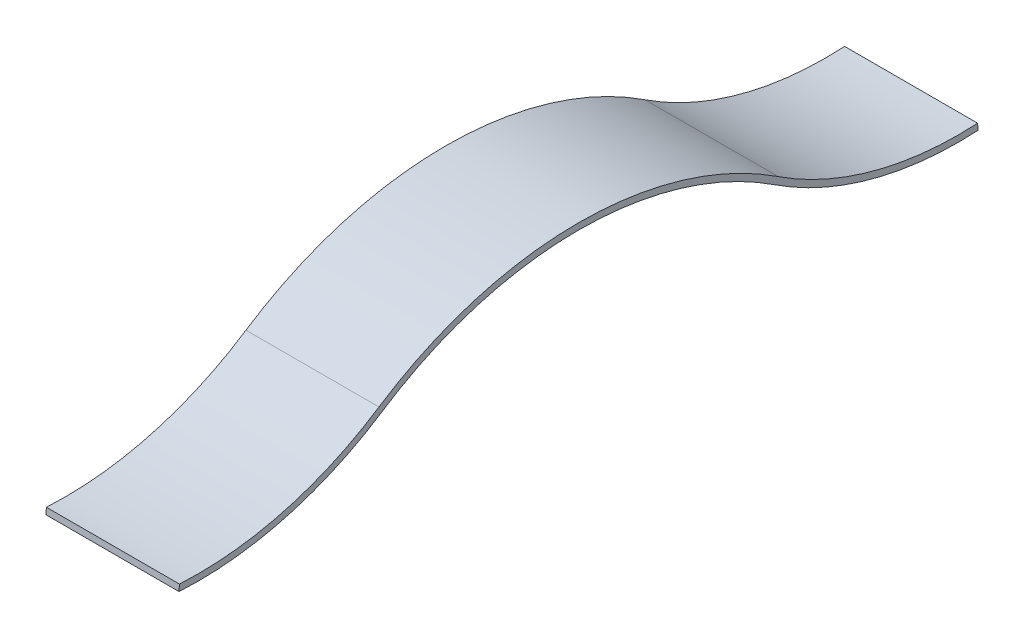
SolidWorks part; units mm, degrees
ref_plane "Front Plane" through (0, 0, 0) normal (0, 0, 1) x (1, 0, 0)
ref_plane "Top Plane" through (0, 0, 0) normal (0, 1, 0) x (1, 0, 0)
ref_plane "Right Plane" through (0, 0, 0) normal (1, 0, 0) x (0, 0, -1)
sketch "Sketch1" plane through (0, 0, 0) normal (1, 0, 0) x (0, 0, -1)
  line L0 (-19.05, 0) -> (19.05, 0) construction
  line L1 (-19.05, 5.4102) -> (19.05, 5.4102) construction
  line L2 (-14.2875, 2.7051) -> (14.2875, 2.7051) construction
  line L3 (0, 5.4102) -> (0, 0) construction
  line L4 (-19.05, 0.3048) -> (-19.05, 0) construction
  line L5 (19.05, 0.3048) -> (19.05, 0) construction
  arc A0 (4.7625, 2.7051) -> (-4.7625, 2.7051) centre (0, 5.5449) cw construction
  arc A1 (-4.7625, 2.7051) -> (-14.2875, 2.7051) centre (-9.525, -0.1347) ccw construction
  arc A2 (-14.2875, 2.7051) -> (-19.05, 0) centre (-19.05, 5.5449) cw construction
  arc A3 (4.7625, 2.7051) -> (14.2875, 2.7051) centre (9.525, -0.1347) cw construction
  arc A4 (14.2875, 2.7051) -> (19.05, 0) centre (19.05, 5.5449) ccw construction
  arc A5 (14.5493, 2.8612) -> (19.05, 0.3048) centre (19.05, 5.5449) ccw construction
  arc A6 (4.5007, 2.8612) -> (14.5493, 2.8612) centre (9.525, -0.1347) cw construction
  arc A7 (4.5007, 2.8612) -> (-4.5007, 2.8612) centre (0, 5.5449) cw construction
  arc A8 (-4.5007, 2.8612) -> (-14.5493, 2.8612) centre (-9.525, -0.1347) ccw construction
  arc A9 (-14.5493, 2.8612) -> (-19.05, 0.3048) centre (-19.05, 5.5449) cw construction
  arc A10 (-9.525, 2.8612) -> (9.525, 2.8612) centre (0, -11.6075) cw
  arc A11 (-19.05, 0.3048) -> (-9.525, 2.8612) centre (-18.1447, 15.9547) ccw
  arc A12 (9.525, 2.8612) -> (19.05, 0.3048) centre (18.1447, 15.9547) ccw
  point P0 (0, 2.7051)
  point P5 (9.525, 5.4102)
  point P6 (0, 0)
  point P10 (0, 2.7051)
  point P16 (-9.525, 5.4102)
  point P33 (-9.525, 5.715)
  point P34 (9.525, 5.715)
  point P37 (0, 5.715)
  dimension "Height" = 5.715
  dimension "LG" = 38.1
  dimension "ThicknessOffset" = 0.3048
extrude "Extrude-Thin1" add sketch "Sketch1" along normal mid plane 6.35 thin
